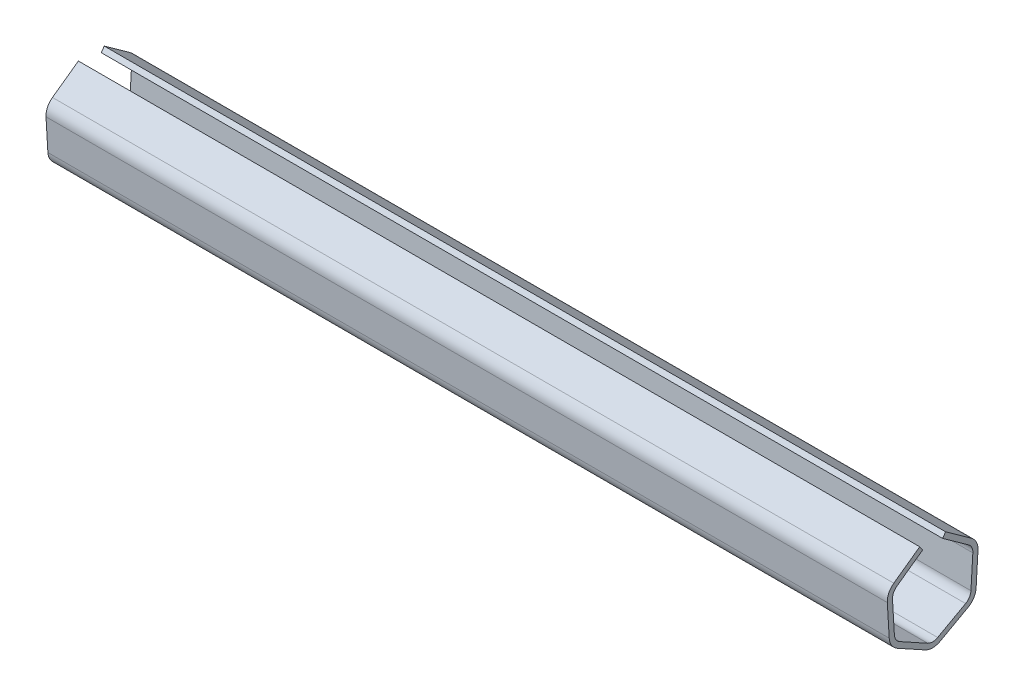
SolidWorks part; units mm, degrees
ref_plane "Front Plane" through (0, 0, 0) normal (0, 0, 1) x (1, 0, 0)
ref_plane "Top Plane" through (0, 0, 0) normal (0, 1, 0) x (1, 0, 0)
ref_plane "Right Plane" through (0, 0, 0) normal (1, 0, 0) x (0, 0, -1)
sketch "Sketch1" plane through (0, 0, 0) normal (1, 0, 0) x (0, 0, -1)
  line L0 (0, -37.8378) -> (0, 0) construction
  line L1 (-5.7943, -34.6429) -> (-27.3812, -22.74)
  line L2 (-33.566, -12.9398) -> (-35.0208, 11.6682)
  line L3 (-30.0339, 22.1289) -> (-10, 36.4925)
  line L4 (-20.017, 29.3107) -> (-34.2934, -0.6358) construction
  line L5 (-34.2934, -0.6358) -> (-16.5877, -28.6914) construction
  line L6 (-16.5877, -28.6914) -> (16.5877, -28.6914) construction
  line L7 (30.0339, 22.1289) -> (10, 36.4925)
  line L8 (33.566, -12.9398) -> (35.0208, 11.6682)
  line L9 (5.7943, -34.6429) -> (27.3812, -22.74)
  line L10 (-10, 36.4925) -> (0, 0) construction
  arc A0 (30.0339, 22.1289) -> (35.0208, 11.6682) centre (23.0418, 12.3764) cw
  arc A1 (33.566, -12.9398) -> (27.3812, -22.74) centre (21.5869, -12.2316) cw
  arc A2 (5.7943, -34.6429) -> (-5.7943, -34.6429) centre (0, -24.1345) cw
  arc A3 (-27.3812, -22.74) -> (-33.566, -12.9398) centre (-21.5869, -12.2316) cw
  arc A4 (-35.0208, 11.6682) -> (-30.0339, 22.1289) centre (-23.0418, 12.3764) cw
  point P15 (35.4114, 18.2734)
  point P18 (33.1754, -19.5451)
  point P24 (-33.1754, -19.5451)
  point P27 (-35.4114, 18.2734)
  dimension "D3" = 12
  dimension "D1" = 75
  dimension "D2" = 20
extrude "Extrude-Thin1" add sketch "Sketch1" along normal mid plane 650 thin
